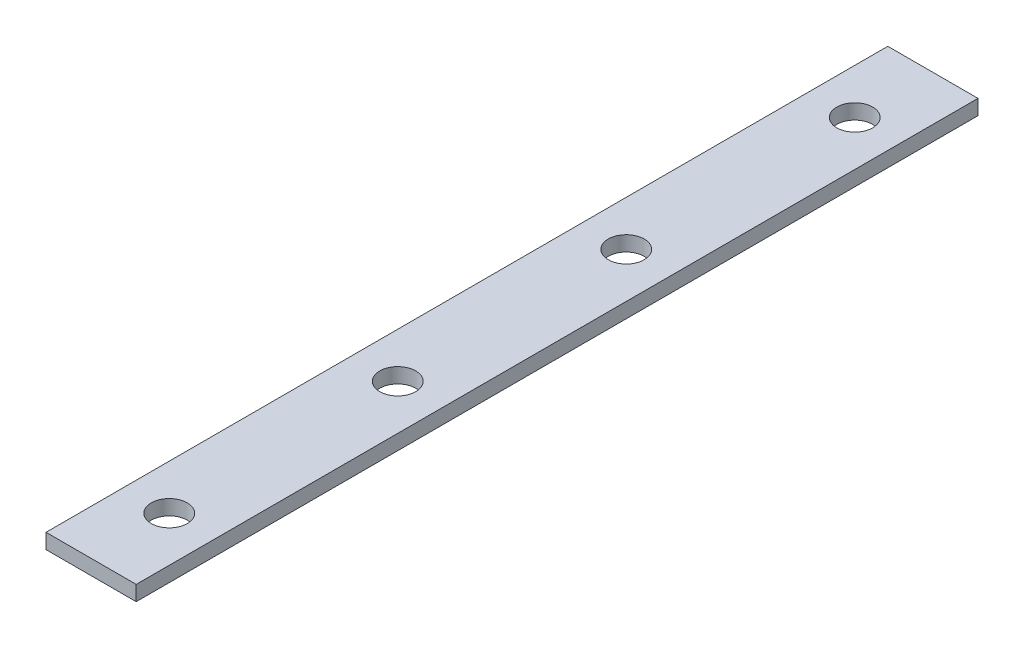
SolidWorks part; units mm, degrees
ref_plane "Front Plane" through (0, 0, 0) normal (0, 0, 1) x (1, 0, 0)
ref_plane "Top Plane" through (0, 0, 0) normal (0, 1, 0) x (1, 0, 0)
ref_plane "Right Plane" through (0, 0, 0) normal (1, 0, 0) x (0, 0, -1)
sketch "Sketch1" plane through (0, 0, 0) normal (0, 1, 0) x (1, 0, 0)
  line L1 (0, 0) -> (9.525, 0)
  line L2 (0, 0) -> (0, 88.9)
  line L3 (0, 88.9) -> (9.525, 88.9)
  line L4 (9.525, 0) -> (9.525, 88.9)
  circle A0 centre (4.7625, 8.255) radius 1.8987
  circle A1 centre (4.7625, 32.385) radius 1.8987
  circle A2 centre (4.7625, 56.515) radius 1.8987
  circle A3 centre (4.7625, 80.645) radius 1.8987
extrude "Boss-Extrude1" add sketch "Sketch1" along normal blind 1.5875
